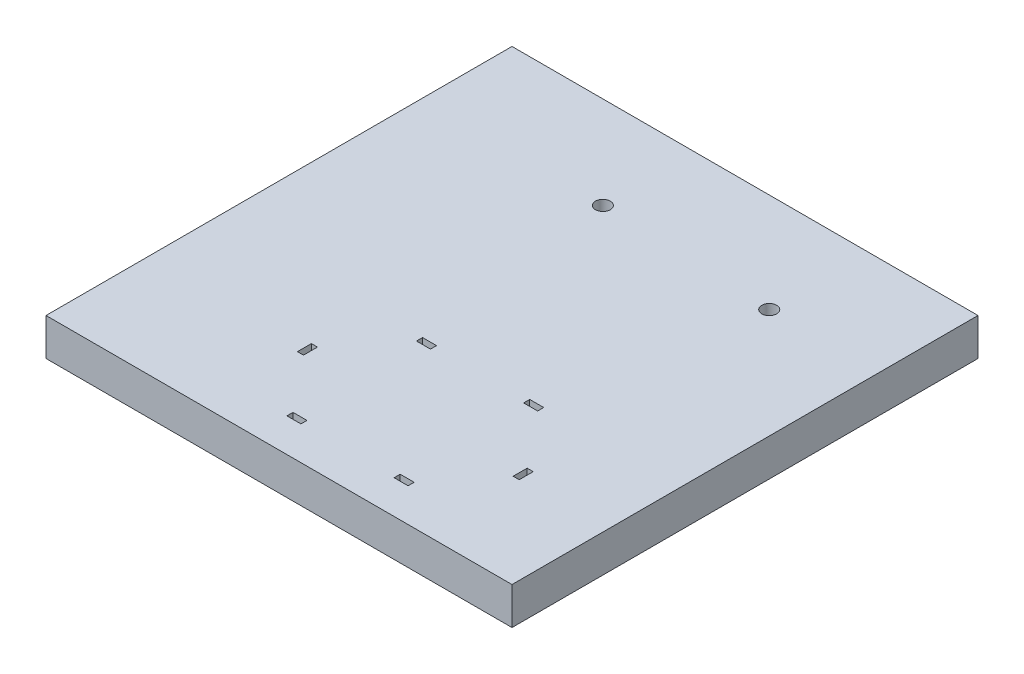
SolidWorks part; units mm, degrees
ref_plane "Front Plane" through (0, 0, 0) normal (0, 0, 1) x (1, 0, 0)
ref_plane "Top Plane" through (0, 0, 0) normal (0, 1, 0) x (1, 0, 0)
ref_plane "Right Plane" through (0, 0, 0) normal (1, 0, 0) x (0, 0, -1)
sketch "Sketch1" plane through (0, 0, 0) normal (0, 1, 0) x (1, 0, 0)
  line L0 (-66.0627, 0) -> (65.2437, 0) construction
  line L1 (-50, 50) -> (50, 50)
  line L2 (-50, 50) -> (-50, -50)
  line L3 (-50, -50) -> (50, -50)
  line L4 (50, 50) -> (50, -50)
  line L5 (7.5, -15) -> (7.5, -41.5) construction
  line L6 (30, 15) -> (-33.5, 15) construction
  line L7 (30, 15) -> (30, 40) construction
  line L8 (30, 40) -> (-33.5, 40) construction
  line L9 (-33.5, 15) -> (-33.5, 40) construction
  line L10 (-15, -15) -> (30, -15) construction
  line L11 (-15, -15) -> (-15, -41.5) construction
  line L12 (-15, -41.5) -> (30, -41.5) construction
  line L13 (30, -15) -> (30, -41.5) construction
  line L14 (-15, -28.25) -> (30, -28.25) construction
  line L15 (20.5, -15) -> (17.5, -15)
  line L16 (-5.5, -15) -> (-2.5, -15)
  line L17 (-5.5, -15) -> (-5.5, -13.7)
  line L18 (-5.5, -13.7) -> (-2.5, -13.7)
  line L19 (-2.5, -15) -> (-2.5, -13.7)
  line L20 (-15, -26.75) -> (-16.3, -26.75)
  line L21 (-15, -26.75) -> (-15, -29.75)
  line L22 (-15, -29.75) -> (-16.3, -29.75)
  line L23 (-16.3, -26.75) -> (-16.3, -29.75)
  line L24 (17.5, -15) -> (17.5, -13.7)
  line L25 (20.5, -13.7) -> (17.5, -13.7)
  line L26 (20.5, -15) -> (20.5, -13.7)
  line L27 (30, -26.75) -> (31.3, -26.75)
  line L28 (31.3, -26.75) -> (31.3, -29.75)
  line L29 (30, -29.75) -> (31.3, -29.75)
  line L30 (30, -26.75) -> (30, -29.75)
  line L31 (17.5, -41.5) -> (17.5, -42.8)
  line L32 (20.5, -41.5) -> (17.5, -41.5)
  line L33 (20.5, -41.5) -> (20.5, -42.8)
  line L34 (20.5, -42.8) -> (17.5, -42.8)
  line L35 (-5.5, -41.5) -> (-2.5, -41.5)
  line L36 (-2.5, -41.5) -> (-2.5, -42.8)
  line L37 (-5.5, -41.5) -> (-5.5, -42.8)
  line L38 (-5.5, -42.8) -> (-2.5, -42.8)
  circle A0 centre (26.5, 28.7) radius 1.6
  circle A1 centre (-10.7, 30.2) radius 1.6
  point P4 (50, 0)
  point P6 (0, 50)
  point P33 (-15, -28.25)
  dimension "D5" = 3.2
  dimension "D10" = 3.2
  dimension "D17" = 3
  dimension "D18" = 1.3
  dimension "D1" = 100
  dimension "D2" = 100
  dimension "D3" = 15
  dimension "D4" = 20
  dimension "D6" = 3.5
  dimension "D7" = 13.7
  dimension "D8" = 63.5
  dimension "D9" = 25
  dimension "D11" = 40.7
  dimension "D12" = 15.2
  dimension "D13" = 26.5
  dimension "D14" = 45
  dimension "D15" = 15
  dimension "D16" = 20
  dimension "D19" = 3
  dimension "D20" = 1.3
  dimension "D21" = 20
extrude "Boss-Extrude1" add sketch "Sketch1" along normal blind 8
